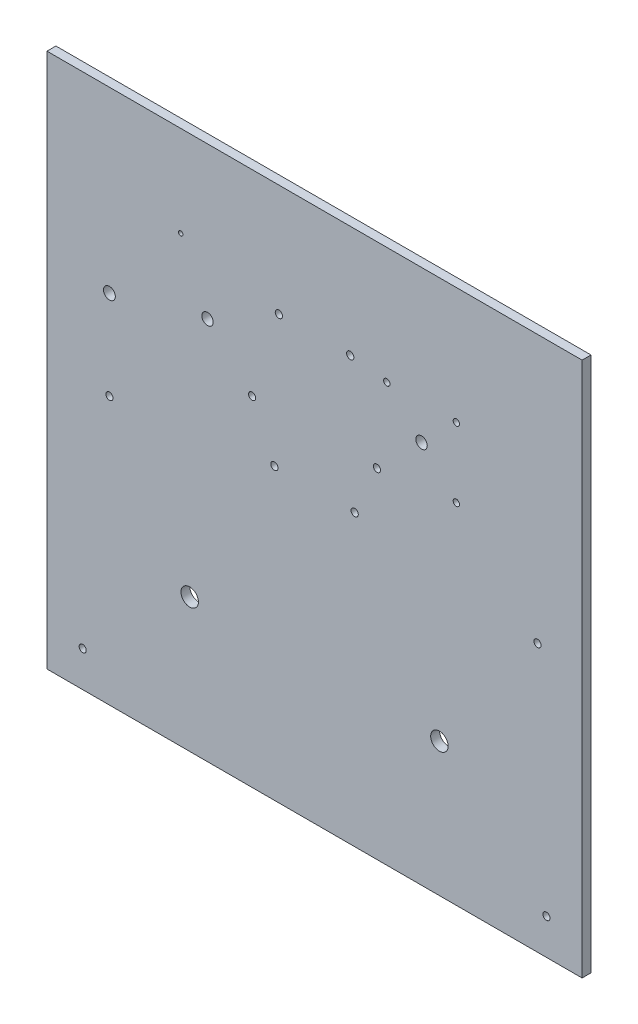
SolidWorks part; units mm, degrees
material "1060 Alloy"
ref_plane "Front Plane" through (0, 0, 0) normal (0, 0, 1) x (1, 0, 0)
ref_plane "Top Plane" through (0, 0, 0) normal (0, 1, 0) x (1, 0, 0)
ref_plane "Right Plane" through (0, 0, 0) normal (1, 0, 0) x (0, 0, -1)
sketch "Sketch1" plane through (0, 0, 0) normal (0, 0, 1) x (1, 0, 0)
  line L0 (-25.4, 301.365) -> (25.4, 301.365) construction
  line L1 (0, 381) -> (0, 0) construction
  line L2 (-146.05, 190.5) -> (-146.05, -8.5714) construction
  line L3 (51.4513, 297.7987) -> (100.9487, 248.3013) construction
  line L4 (76.2, 273.05) -> (100.9487, 297.7987) construction
  line L6 (190.5, 381) -> (-190.5, 381)
  line L10 (-76.2, 273.05) -> (76.2, 273.05) construction
  line L11 (-44.45, 241.3) -> (44.45, 241.3) construction
  line L12 (-28.575, 206.115) -> (28.575, 206.115) construction
  line L13 (190.5, 381) -> (190.5, 0)
  line L14 (-190.5, 381) -> (-190.5, 0)
  line L16 (-190.5, 0) -> (190.5, 0)
  circle A0 centre (76.2, 273.05) radius 4.064
  circle A1 centre (44.45, 241.3) radius 2.54
  circle A2 centre (88.9, 95.25) radius 6.223
  circle A3 centre (-165.1, 25.4) radius 2.54
  circle A4 centre (100.9487, 297.7987) radius 2.25
  circle A5 centre (158.75, 190.5) radius 2.54
  circle A6 centre (51.4513, 297.7987) radius 2.25
  circle A7 centre (165.1, 25.4) radius 2.54
  circle A8 centre (-88.9, 95.25) radius 6.223
  circle A9 centre (28.575, 206.115) radius 2.5797
  circle A10 centre (-146.05, 190.5) radius 2.54
  circle A12 centre (-25.4, 301.365) radius 2.5797
  circle A13 centre (25.4, 301.365) radius 2.5797
  circle A14 centre (-44.45, 241.3) radius 2.54
  circle A15 centre (-76.2, 273.05) radius 4.064
  circle A16 centre (-28.575, 206.115) radius 2.5797
  circle A17 centre (-95.25, 316.23) radius 1.5875
  circle A19 centre (100.9487, 248.3013) radius 2.25
  circle A20 centre (51.4513, 248.3013) radius 2.25 [skipped]
  point P4 (0, 301.365)
  point P6 (0, 241.3)
  point P18 (0, 273.05)
  point P38 (0, 206.115)
  dimension "D2" = 50.8
  dimension "D3" = 57.15
  dimension "D18" = 5.1594
  dimension "D13" = 4
  dimension "D4" = 381
  dimension "D5" = 381
  dimension "D6" = 25.4
  dimension "D7" = 25.4
  dimension "D8" = 95.25
  dimension "D9" = 101.6
  dimension "D10" = 190.5
  dimension "D11" = 44.45
  dimension "D12" = 114.3
  dimension "D14" = 49.4975
  dimension "D15" = 273.05
  dimension "D16" = 241.3
  dimension "D17" = 146.05
  dimension "D19" = 316.23
  dimension "D20" = 95.25
  dimension "D21" = 31.75
  dimension "D22" = 190.5
  dimension "D23" = 95.25
extrude "Boss-Extrude1" add sketch "Sketch1" along normal blind 6.35
hole_wizard "3/8-24 Tapped Hole2" positions "Sketch5" profile "Sketch4" tap size "3/8-24" standard "Ansi Inch" end condition through all
sketch "Sketch5" plane through (0, 0, 6.35) normal (0, 0, 1) x (1, 0, 0)
  line L0 (-146.05, 190.5) -> (-146.05, 254) construction
  point P0 (-146.05, 254)
  dimension "D1" = 63.5
sketch "Sketch4" plane through (-146.05, 254, 6.35) normal (1, 0, 0) x (0, -1, 0)
  line L0 (0, 0) -> (0, 6.35)
  line L1 (0, 6.35) -> (4.2164, 6.35)
  line L2 (4.2164, 6.35) -> (4.2164, 0)
  line L5 (4.2164, 0) -> (0, 0)
  line L11 (0, -6.35) -> (0, 107.95) construction
  dimension "Thru Tap Drill Dia." = 8.4328
  dimension "Thru Tap Drill Depth" = 6.35
cosmetic thread "Hole Thread1" parameters "D2"=9.525
